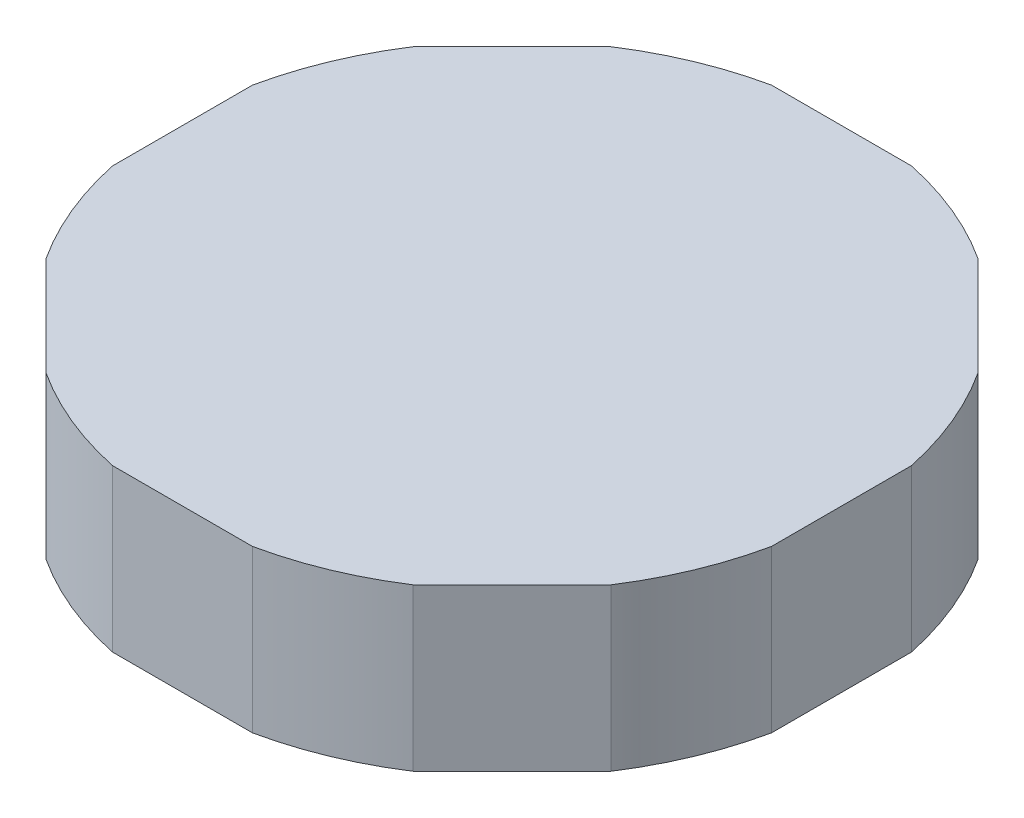
SolidWorks part; units mm, degrees
ref_plane "Front Plane" through (0, 0, 0) normal (0, 0, 1) x (1, 0, 0)
ref_plane "Top Plane" through (0, 0, 0) normal (0, 1, 0) x (1, 0, 0)
ref_plane "Right Plane" through (0, 0, 0) normal (1, 0, 0) x (0, 0, -1)
sketch "Sketch1" plane through (0, 0, 0) normal (0, 1, 0) x (1, 0, 0)
  line L0 (6.1213, 1.3) -> (6.1213, -1.3) construction
  line L1 (26, -1.3) -> (26, 1.3) construction
  circle A0 centre (0, 0) radius 6.2578
extrude "Boss-Extrude1" add sketch "Sketch1" along normal blind 3
sketch "Sketch2" plane through (0, 3, 0) normal (0, 1, 0) x (1, 0, 0)
  line L0 (6.1213, 1.3) -> (6.1213, -1.3) construction
  line L1 (6.1213, -2.5355) -> (6.1213, 2.5355)
  line L2 (6.1213, 2.5355) -> (2.5355, 6.1213)
  line L3 (2.5355, 6.1213) -> (-2.5355, 6.1213)
  line L4 (-2.5355, 6.1213) -> (-6.1213, 2.5355)
  line L5 (-6.1213, 2.5355) -> (-6.1213, -2.5355)
  line L6 (-6.1213, -2.5355) -> (-2.5355, -6.1213)
  line L7 (-2.5355, -6.1213) -> (2.5355, -6.1213)
  line L8 (2.5355, -6.1213) -> (6.1213, -2.5355)
  circle A0 centre (0, 0) radius 6.1213 construction
  circle A1 centre (0, 0) radius 8.1213
  dimension "D1" = 2
extrude "Cut-Extrude1" cut sketch "Sketch2" against normal through all
